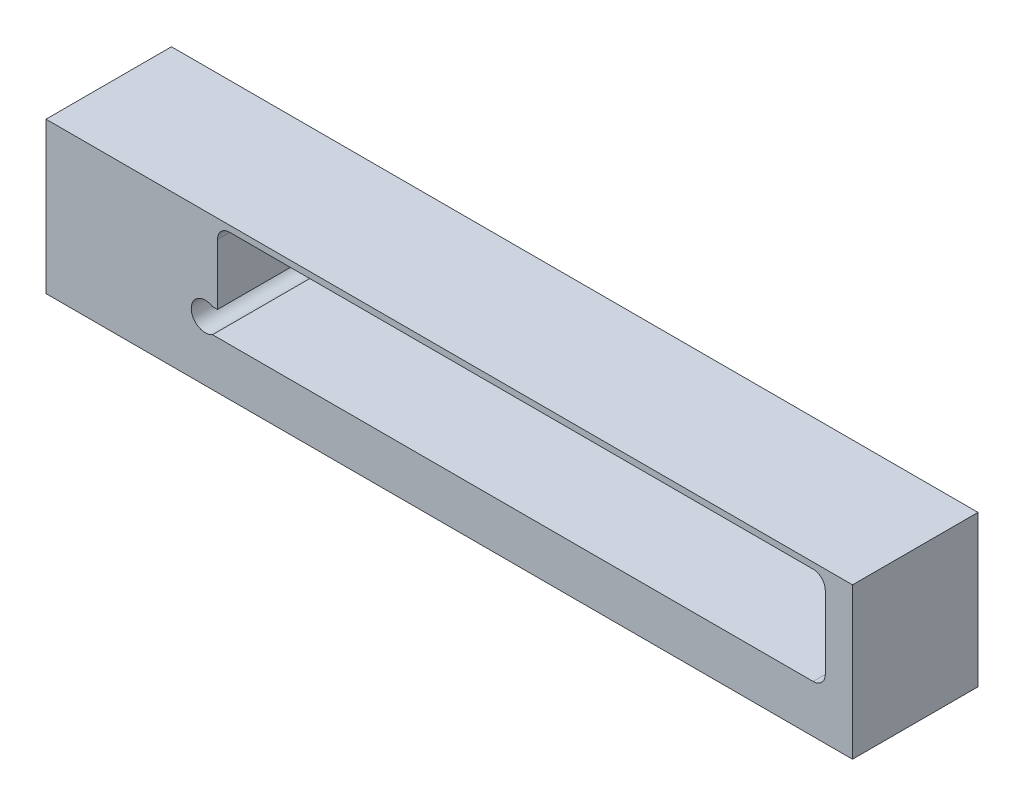
SolidWorks part; units mm, degrees
ref_plane "Front Plane" through (0, 0, 0) normal (0, 0, 1) x (1, 0, 0)
ref_plane "Top Plane" through (0, 0, 0) normal (0, 1, 0) x (1, 0, 0)
ref_plane "Right Plane" through (0, 0, 0) normal (1, 0, 0) x (0, 0, -1)
sketch "Sketch1" plane through (0, 0, 0) normal (0, 0, 1) x (1, 0, 0)
  line L0 (0, 0) -> (0, 152.64) construction
  line L1 (-406.4, -152.64) -> (406.4, -152.64)
  line L2 (-406.4, -152.64) -> (-406.4, 152.64)
  line L5 (-406.4, -152.64) -> (406.4, 152.64) construction
  line L6 (-406.4, 152.64) -> (406.4, -152.64) construction
  line L7 (0, 152.64) -> (0, 95.04)
  line L8 (0, 0) -> (406.4, 0) construction
  line L9 (-406.4, 152.64) -> (-406.4, 232.64)
  line L10 (-406.4, 232.64) -> (1650.5081, 232.64)
  line L11 (406.4, -152.64) -> (1650.5081, -152.64)
  line L12 (1650.5081, -152.64) -> (1650.5081, 232.64)
  circle A0 centre (0, 0) radius 36
  circle A1 centre (0, 95.04) radius 20.52
  circle A2 centre (0, -95.04) radius 20.52
  point P0 (0, 0)
extrude "Boss-Extrude1" add sketch "Sketch1" along normal blind 320
sketch "Sketch2" plane through (0, 0, 320) normal (0, 0, 1) x (1, 0, 0)
  line L0 (258.5862, -31) -> (258.5862, 217) construction
  line L14 (31, 0) -> (62, 0) construction
  line L15 (1581, 186) -> (1550, 186) construction
  line L16 (1581, 0) -> (1581, 186)
  line L17 (31, 0) -> (62, 0) construction
  line L18 (1519, 0) -> (1550, 0) construction
  line L19 (62, 217) -> (1550, 217)
  line L20 (18.303, -31) -> (1550, -31)
  line L21 (31, 186) -> (31, 53.4696)
  line L22 (18.303, 31) -> (31, 31)
  line L23 (31, 31) -> (31, 53.4696)
  arc A2 (1550, -31) -> (1581, 0) centre (1550, 0) ccw
  arc A3 (1581, 186) -> (1550, 217) centre (1550, 186) ccw
  arc A4 (62, 217) -> (31, 186) centre (62, 186) ccw
  arc A5 (18.303, -31) -> (18.303, 31) centre (0, 0) ccw
  circle M2 centre (0, 0) radius 36
extrude "Cut-Extrude1" cut sketch "Sketch2" against normal blind 310 contours L19 A4 L21 L23 L22 L20 A2 L16 A3 M2
sketch "Sketch3" plane through (0, 0, 320) normal (0, 0, 1) x (1, 0, 0)
  circle A0 centre (0, 95.04) radius 20.52
  circle A1 centre (0, -95.04) radius 20.52
extrude "Boss-Extrude2" add sketch "Sketch3" against normal blind 155
